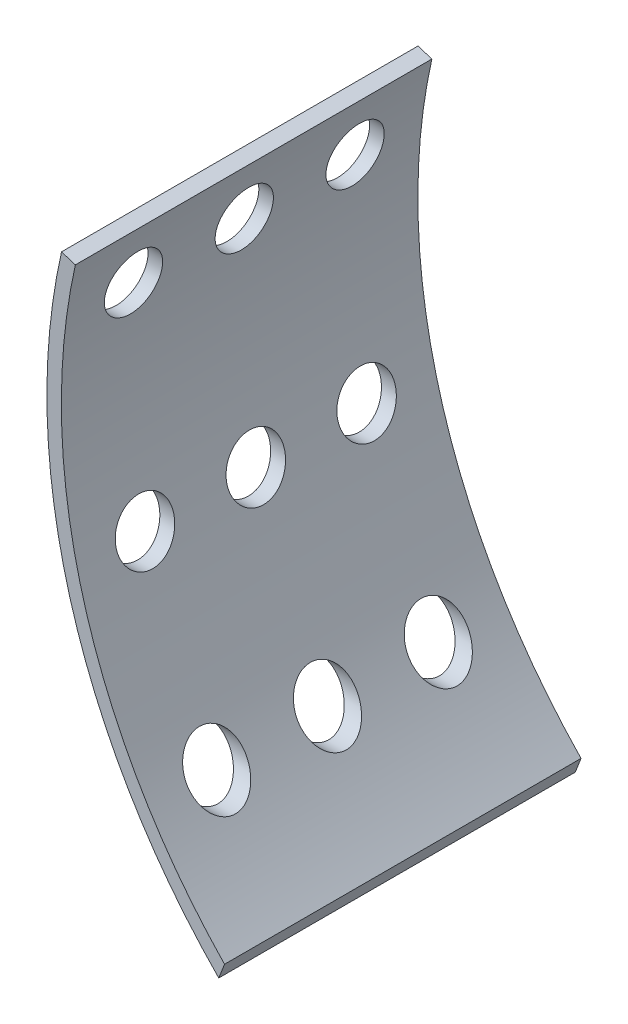
SolidWorks part; units mm, degrees
material "AISI 1020"
ref_plane "Ön Düzlem" through (0, 0, 0) normal (0, 0, 1) x (1, 0, 0)
ref_plane "Üst Düzlem" through (0, 0, 0) normal (0, 1, 0) x (1, 0, 0)
ref_plane "Sağ Düzlem" through (0, 0, 0) normal (1, 0, 0) x (0, 0, -1)
sketch "Model" plane through (0, 0, 0) normal (0, 0, 1) x (1, 0, 0)
  line L0 (2607.29, 2081.1259) -> (2592.9332, 2085.655)
  line L1 (2756.1391, 1514.5545) -> (2762.1125, 1529.913)
  arc A0 (2607.29, 2081.1259) -> (2762.1125, 1529.913) centre (3197.094, 1949.4384) ccw
  arc A1 (2592.9332, 2085.655) -> (2756.1391, 1514.5545) centre (3197.094, 1949.4384) ccw
extrude "Yükseklik-Ekstrüzyon1" add sketch "Model" along normal blind 370
sketch "Sketch1" plane through (0, 0, 0) normal (1, 0, 0) x (0, 0, -1)
  line L0 (-370, 2085.655) -> (0, 2085.655) construction
  line L1 (0, 1514.5545) -> (0, 2085.655) construction
  line L2 (-370, 2085.655) -> (-370, 1514.5545) construction
  circle A1 centre (-300, 2025.655) radius 30
  circle A2 centre (-185, 2025.655) radius 30
  circle A3 centre (-70, 2025.655) radius 30
  circle A4 centre (-300, 1808.1527) radius 30
  circle A5 centre (-185, 1808.1527) radius 30
  circle A6 centre (-70, 1808.1527) radius 30
  circle A7 centre (-300, 1630.7622) radius 30
  circle A8 centre (-185, 1630.7622) radius 30
  circle A9 centre (-70, 1630.7622) radius 30
  dimension "D1" = 60
  dimension "D2" = 60
  dimension "D3" = 60
  dimension "D5" = 60
  dimension "D6" = 60
  dimension "D8" = 185
  dimension "D10" = 60
  dimension "D11" = 60
  dimension "D12" = 60
  dimension "D13" = 60
  dimension "D14" = 60
  dimension "D15" = 60
  dimension "D4" = 60
  dimension "D7" = 70
  dimension "D9" = 70
extrude "Cut-Extrude3" cut sketch "Sketch1" along normal through all contours A2 | A1 | A3 | A4 | A5 | A6 | A7 | A8 | A9
